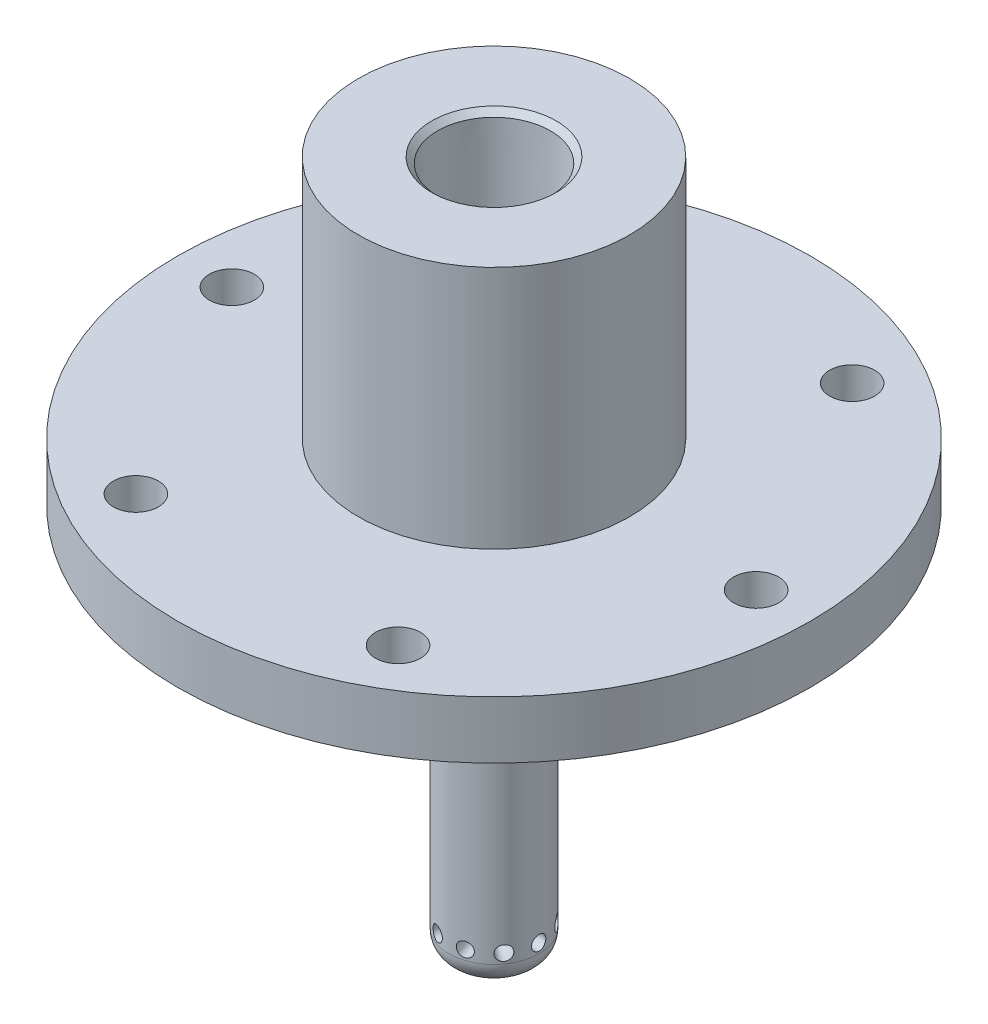
SolidWorks part; units mm, degrees
ref_plane "Front Plane" through (0, 0, 0) normal (0, 0, 1) x (1, 0, 0)
ref_plane "Top Plane" through (0, 0, 0) normal (0, 1, 0) x (1, 0, 0)
ref_plane "Right Plane" through (0, 0, 0) normal (1, 0, 0) x (0, 0, -1)
sketch "Sketch1" plane through (0, 0, 0) normal (0, 0, 1) x (1, 0, 0)
  line L0 (0, 0) -> (-15, 0)
  line L1 (-15, 0) -> (-15, -27)
  line L2 (-15, -27) -> (-35, -27)
  line L3 (-35, -27) -> (-35, -33.35)
  line L4 (-35, -33.35) -> (-16, -33.35)
  line L5 (-10, -37.35) -> (-10, -41.35)
  line L6 (-10, -41.35) -> (-5, -46.35)
  line L7 (-5, -46.35) -> (-5, -73.85)
  line L8 (-2.5, -76.35) -> (0, -76.35)
  line L9 (0, -76.35) -> (0, 0)
  line L11 (-10, -37.35) -> (-16, -37.35)
  line L12 (-16, -37.35) -> (-16, -33.35)
  arc A0 (-5, -73.85) -> (-2.5, -76.35) centre (-2.5, -73.85) ccw
  point P7 (-10, -33.35)
  point P15 (-5, -76.35)
  dimension "D9" = 2.5
  dimension "D1" = 5
  dimension "D2" = 10
  dimension "D3" = 30
  dimension "D4" = 45
  dimension "D5" = 6.35
  dimension "D6" = 8
  dimension "D7" = 15
  dimension "D8" = 25
  dimension "D11" = 4
  dimension "D10" = 27
  dimension "D12" = 16
revolve "Revolve1" add sketch "Sketch1" angle 360 about L9
hole_wizard "#10 Clearance Hole2" positions "Sketch14" profile "Sketch15" hole size "#10" standard "ANSI Inch"
sketch "Sketch14" plane through (0, 0, 0) normal (0, 1, 0) x (1, 0, 0)
  point P0 (0, 0)
sketch "Sketch15" plane through (0, 0, 0) normal (1, 0, 0) x (0, 0, 1)
  line L0 (0, 0) -> (0, 74.9957)
  line L1 (0, 74.9957) -> (2.4892, 73.5)
  line L2 (2.4892, 73.5) -> (2.4892, 0)
  line L5 (2.4892, 0) -> (0, 0)
  line L10 (0, 74.9957) -> (-2.4892, 73.5) construction
  line L11 (0, -6.35) -> (0, 107.95) construction
  dimension "Hole Dia." = 4.9784
  dimension "Hole Depth" = 73.5
  dimension "Drill Angle" = 118
hole_wizard "1/4 NPT Tapped Hole0" positions "Sketch2" profile "Sketch4" size "1/4" standard "ANSI Inch"
sketch "Sketch2" plane through (0, 0, 0) normal (0, 1, 0) x (1, 0, 0)
  point P0 (0, 0)
cosmetic thread "Hole Thread1" parameters "D1"=10.02, "D2"=13.7154
sketch "Sketch4" plane through (0, 0, 0) normal (1, 0, 0) x (0, 0, 1)
  line L0 (0, 0) -> (0, 20.4123)
  line L1 (5.5626, 17.07) -> (0, 20.4123)
  line L2 (-5.5626, 17.07) -> (0, 20.4123) construction
  line L3 (5.5626, 17.07) -> (5.5626, 10.02)
  line L4 (5.5626, 10.02) -> (5.9627, 10.02)
  line L5 (5.9627, 10.02) -> (6.2437, 0.635)
  line L6 (6.2437, 0.635) -> (6.8787, 0)
  line L7 (6.8787, 0) -> (0, 0)
  line L8 (0, -6.35) -> (0, 107.95) construction
  line L9 (-6.2437, 0.635) -> (-6.8787, 0) construction
  line L11 (-5.5626, 10.02) -> (-5.9627, 10.02) construction
  line L12 (-5.9627, 10.02) -> (-6.2437, 0.635) construction
  dimension "Tap Drill Dia." = 11.1252
  dimension "Tap Drill Depth" = 17.07
  dimension "Thread Dia." = 12.4874
  dimension "Thread Angle" = 3.43
  dimension "Thread Depth" = 10.02
  dimension "C'Sink Dia." = 13.7574
  dimension "C'Sink Angle" = 90
  dimension "Drill Angle" = 118
hole_wizard "#10 Clearance Hole1" positions "Sketch6" profile "Sketch8" hole size "#10" standard "ANSI Inch" end condition through all
sketch "Sketch6" plane through (0, -27, 0) normal (0, 1, 0) x (1, 0, 0)
  point P0 (29, 0)
  dimension "D1" = 29
sketch "Sketch8" plane through (29, -27, 0) normal (1, 0, 0) x (0, 0, 1)
  line L0 (0, 0) -> (0, 49.35)
  line L1 (0, 49.35) -> (2.4892, 49.35)
  line L2 (2.4892, 49.35) -> (2.4892, 0)
  line L5 (2.4892, 0) -> (0, 0)
  line L11 (0, -6.35) -> (0, 107.95) construction
  dimension "Thru Hole Dia." = 4.9784
  dimension "Thru Hole Depth" = 49.35
sketch "Sketch5" plane through (0, -33.35, 0) normal (0, -1, 0) x (-1, 0, 0)
  circle A0 centre (0, 0) radius 20.32
  circle A1 centre (0, 0) radius 24.384
  dimension "D1" = 40.64
  dimension "D2" = 48.768
extrude "Cut-Extrude1" cut sketch "Sketch5" against normal blind 2.667
pattern_circular "CirPattern1" count 6 over 360 about axis through (0, 0, 0) along (0, 1, 0) of "#10 Clearance Hole1"
sketch "Sketch13" plane through (0, 0, 0) normal (0, 1, 0) x (1, 0, 0)
  point P0 (0, 0)
ref_plane "Plane1" through (5, 0, 0) normal (1, 0, 0) x (0, 0, -1)
hole_wizard "1/16 (0.0625) Diameter Hole1" positions "Sketch18" profile "Sketch19" hole size "1/16" standard "ANSI Inch" end condition through all
sketch "Sketch18" plane through (5, 0, 0) normal (1, 0, 0) x (0, 0, -1)
  line L0 (5, -73.85) -> (-5, -73.85) construction
  point P0 (0, -72.8)
  dimension "D1" = 1.05
sketch "Sketch19" plane through (5, -72.8, 0) normal (0, 1, 0) x (0, 0, -1)
  line L0 (0, 0) -> (0, 40)
  line L1 (0, 40) -> (0.7937, 40)
  line L2 (0.7937, 40) -> (0.7937, 0)
  line L5 (0.7937, 0) -> (0, 0)
  line L11 (0, -6.35) -> (0, 107.95) construction
  dimension "Thru Hole Dia." = 1.5875
  dimension "Thru Hole Depth" = 40
pattern_circular "CirPattern3" count 5 over 360 about axis through (0, -73.85, 0) along (0, -1, 0) of "1/16 (0.0625) Diameter Hole1"
fillet "Fillet1" radius 0.508 2 edges at (0, -30.683, -24.384) (0, -30.683, -20.32)
fillet "Fillet2" radius 0.127 2 edges at (0, -33.35, -24.384) (0, -33.35, -20.32)
